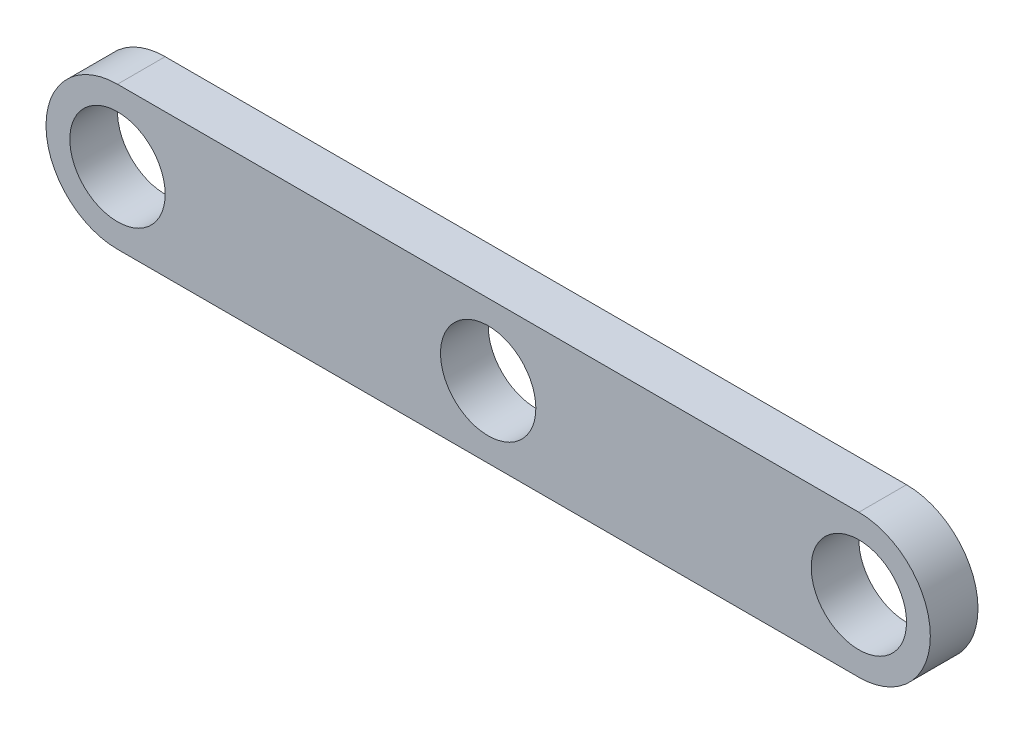
SolidWorks part; units mm, degrees
ref_plane "Front Plane" through (0, 0, 0) normal (0, 0, 1) x (1, 0, 0)
ref_plane "Top Plane" through (0, 0, 0) normal (0, 1, 0) x (1, 0, 0)
ref_plane "Right Plane" through (0, 0, 0) normal (1, 0, 0) x (0, 0, -1)
sketch "Sketch1" plane through (0, 0, 0) normal (0, 0, 1) x (1, 0, 0)
  line L0 (-77.7782, 0) -> (77.7782, 0) construction
  line L1 (-77.7782, 15) -> (77.7782, 15)
  line L2 (-77.7782, -15) -> (77.7782, -15)
  arc A0 (-77.7782, 15) -> (-77.7782, -15) centre (-77.7782, 0) ccw
  arc A1 (77.7782, -15) -> (77.7782, 15) centre (77.7782, 0) ccw
  circle A2 centre (-77.7782, 0) radius 10
  circle A3 centre (77.7782, 0) radius 10
  circle A4 centre (0, 0) radius 10
  point P3 (0, 0)
extrude "Boss-Extrude1" add sketch "Sketch1" along normal blind 10
